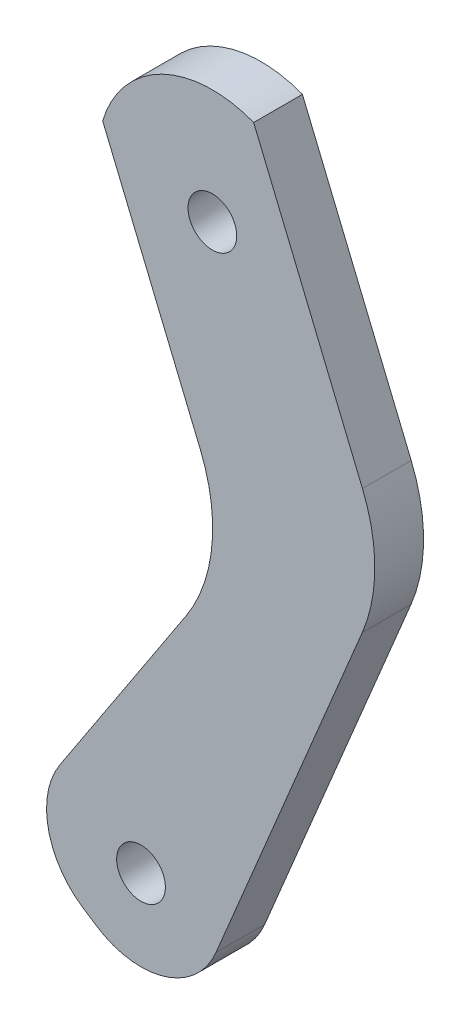
SolidWorks part; units mm, degrees
ref_plane "Front" through (0, 0, 0) normal (0, 0, 1) x (1, 0, 0)
ref_plane "Top" through (0, 0, 0) normal (0, 1, 0) x (1, 0, 0)
ref_plane "Right" through (0, 0, 0) normal (1, 0, 0) x (0, 0, -1)
ref_axis "Axis1" through (0, 0, -80.9) along (0, 0, 1)
sketch "草图1" plane through (0, 0, 0) normal (0, 0, 1) x (1, 0, 0)
  circle A0 centre (0, 0) radius 18
extrude "LaShenA" add sketch "草图1" along normal blind 30
sketch "SketchA" plane through (0, 0, 30) normal (0, 0, 1) x (1, 0, 0)
  line L0 (0, 0) -> (0, 18) construction
  arc A0 (0.4232, 13.4934) -> (-0.4232, 13.4934) centre (0, 0) ccw
  arc A1 (3.858, 18.7275) -> (-3.858, 18.7275) centre (0, 0) ccw
  arc A2 (-0.4232, 13.4934) -> (-1.2044, 14.1898) centre (-0.447, 14.253) cw
  arc A3 (1.2044, 14.1898) -> (0.4232, 13.4934) centre (0.447, 14.253) cw
  circle A4 centre (0, 0) radius 15.0351 construction
  circle A5 centre (0, 0) radius 18 construction
  circle A6 centre (0, 0) radius 13.5 construction
  circle A7 centre (0, 0) radius 16 construction
  spline S0 degree 3 poles (1.2044, 14.1898) (1.2266, 14.4552) (1.2138, 14.7739) (1.2737, 15.1106) (1.2991, 15.2114) (1.3214, 15.2911) (1.3499, 15.3823) (1.3851, 15.4846) (1.4278, 15.5978) (1.4786, 15.7214) (1.5382, 15.8552) (1.6071, 15.9987) (1.686, 16.1514) (1.7754, 16.3129) (1.876, 16.4827) (1.9884, 16.6603) (2.1129, 16.8451) (2.2502, 17.0365) (2.4007, 17.234) (2.5649, 17.4369) (2.7432, 17.6446) (2.9361, 17.8564) (3.1439, 18.0718) (3.4474, 18.3685) (3.6895, 18.585) (3.858, 18.7275) knots 0.122308 0.122308 0.122308 0.122308 0.250611 0.276296 0.287604 0.300968 0.316388 0.333864 0.353395 0.374983 0.398627 0.424327 0.452082 0.481894 0.513762 0.547685 0.583665 0.6217 0.661792 0.703939 0.748143 0.794402 0.842718 0.893089 1 1 1 1
  spline S1 degree 3 poles (-1.2044, 14.1898) (-1.2266, 14.4552) (-1.2138, 14.7739) (-1.2737, 15.1106) (-1.2991, 15.2114) (-1.3214, 15.2911) (-1.3499, 15.3823) (-1.3851, 15.4846) (-1.4278, 15.5978) (-1.4786, 15.7214) (-1.5382, 15.8552) (-1.6071, 15.9987) (-1.686, 16.1514) (-1.7754, 16.3129) (-1.876, 16.4827) (-1.9884, 16.6603) (-2.1129, 16.8451) (-2.2502, 17.0365) (-2.4007, 17.234) (-2.5649, 17.4369) (-2.7432, 17.6446) (-2.9361, 17.8564) (-3.1439, 18.0718) (-3.4474, 18.3685) (-3.6895, 18.585) (-3.858, 18.7275) knots 0.122308 0.122308 0.122308 0.122308 0.250611 0.276296 0.287604 0.300968 0.316388 0.333864 0.353395 0.374983 0.398627 0.424327 0.452082 0.481894 0.513762 0.547685 0.583665 0.6217 0.661792 0.703939 0.748143 0.794402 0.842718 0.893089 1 1 1 1
  dimension "D1" = 0.76
  dimension "Db" = 30.0702
  dimension "Da" = 36
  dimension "Df" = 27
  dimension "Dn" = 32
extrude "Cut-ExtrudeA" cut sketch "SketchA" against normal blind 30
pattern_circular "www.KYTool.cn" count 16 over 360 about axis through (0, 0, -80.9) along (0, 0, 1) of "Cut-ExtrudeA"
sketch "草图3" plane through (0, 0, 0) normal (0, 1, 0) x (1, 0, 0)
  line L0 (17.7715, -30) -> (17.7715, 0) construction
  line L1 (-17.7715, 0) -> (17.7715, 0)
  line L2 (-17.7715, 0) -> (-17.7715, -27)
  line L3 (-17.7715, -27) -> (17.7715, -27)
  line L4 (17.7715, 0) -> (17.7715, -27)
extrude "切除-拉伸2" cut sketch "草图3" against normal mid plane 60
sketch "草图4" plane through (0, 0, 30) normal (0, 0, 1) x (1, 0, 0)
  circle A0 centre (0, 0) radius 1.5
extrude "切除-拉伸3" cut sketch "草图4" against normal blind 60
sketch "草图5" plane through (0, 0, 30) normal (0, 0, 1) x (1, 0, 0)
  line L2 (0, -13.5) -> (9.5459, -9.5459)
  line L4 (15.2802, -61.8354) -> (7.5186, -73.6486)
  line L10 (0, -13.5) -> (9.5459, -9.5459)
  line L11 (0, -13.5) -> (16.1616, -52.5174)
  line L12 (9.5459, -9.5459) -> (26.1422, -49.6129)
  line L15 (8.9517, -80.5729) -> (9.7653, -81.1075)
  line L16 (26.1308, -57.2939) -> (17.1246, -78.8558)
  arc A2 (-0.4232, -13.4934) -> (0.4232, -13.4934) centre (0, 0) ccw construction
  arc A3 (9.242, -9.8405) -> (9.8405, -9.242) centre (0, 0) ccw construction
  arc A4 (16.1616, -52.5174) -> (15.2802, -61.8354) centre (6.9228, -56.3443) cw
  arc A5 (26.1308, -57.2939) -> (26.1422, -49.6129) centre (16.9034, -53.4397) ccw
  arc A6 (9.7653, -81.1075) -> (17.1246, -78.8558) centre (12.5109, -76.9288) ccw
  arc A7 (7.5186, -73.6486) -> (8.9517, -80.5729) centre (11.6973, -76.3942) ccw
  circle A8 centre (12.5109, -76.9288) radius 1.5
  circle A9 centre (16.9034, -40.0175) radius 1.5
extrude "凸台-拉伸3" add sketch "草图5" against normal blind 3 contours L4 A7 L15 A6 L16 A5 L12 L2 L11 A4 A9 A8
sketch "草图8" plane through (0, 0, 30) normal (0, 0, 1) x (1, 0, 0)
  line L0 (9.8572, -40.0175) -> (-47.4491, -4.1824)
  line L1 (-47.4491, -4.1824) -> (-5.431, 32.9958)
  line L2 (-5.431, 32.9958) -> (66.6398, 3.8332)
  line L3 (66.6398, 3.8332) -> (22.1887, -35.3576)
  circle A0 centre (16.9034, -40.0175) radius 7.0462
extrude "切除-拉伸5" cut sketch "草图8" against normal blind 3 contours A0 L3 L2 L1 L0
